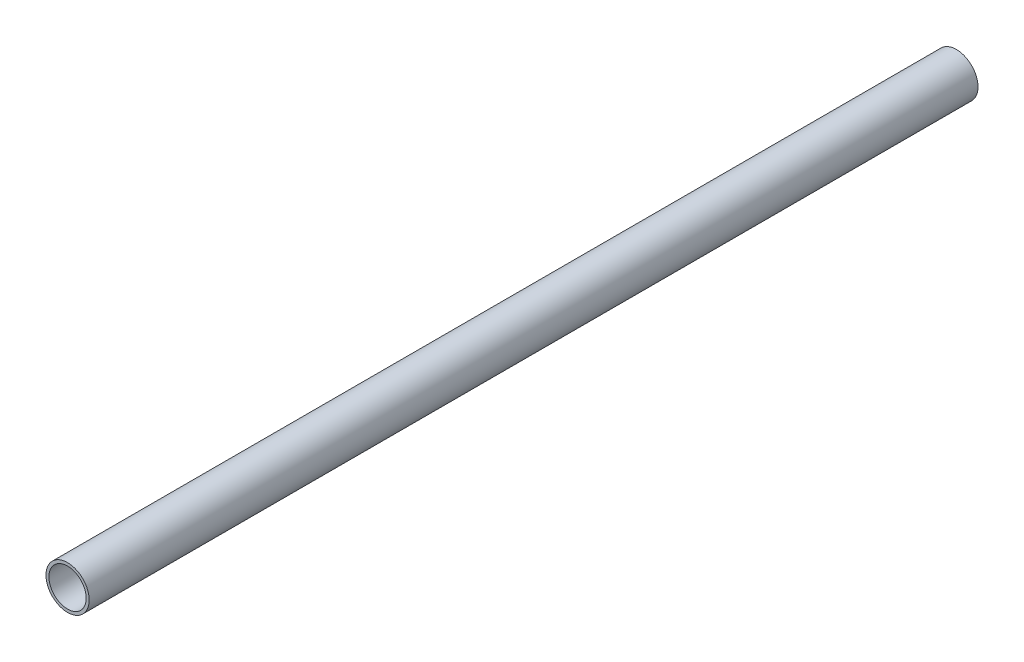
SolidWorks part; units mm, degrees
ref_plane "Front Plane" through (0, 0, 0) normal (0, 0, 1) x (1, 0, 0)
ref_plane "Top Plane" through (0, 0, 0) normal (0, 1, 0) x (1, 0, 0)
ref_plane "Right Plane" through (0, 0, 0) normal (1, 0, 0) x (0, 0, -1)
sketch "Sketch1" plane through (0, 0, 0) normal (0, 0, 1) x (1, 0, 0)
  circle A0 centre (0, 0) radius 22.225 construction
  circle A1 centre (0, 0) radius 19.177 construction
  point P3 (-22.225, 0)
  point P4 (22.225, 0)
  point P6 (-19.177, 0)
  point P7 (19.177, 0)
  dimension "OD" = 44.45
  dimension "Wall" = 3.048
  dimension "ID" = 38.354
sketch "Sketch2" plane through (0, 0, 0) normal (1, 0, 0) x (0, 0, -1)
  line L0 (457.2, 0) -> (-457.2, 0) construction
  line L2 (0, 22.225) -> (0, -22.225) construction
  line L3 (0, 22.225) -> (0, -22.225) construction
  line L4 (457.2, 22.225) -> (-457.2, 22.225) construction
  line L5 (457.2, -22.225) -> (-457.2, -22.225) construction
  line L6 (-457.2, -22.225) -> (-457.2, 22.225) construction
  line L7 (457.2, -22.225) -> (457.2, 22.225) construction
  line L8 (-412.75, -22.225) -> (-412.75, 22.225) construction
  line L9 (412.75, -22.225) -> (412.75, 22.225) construction
  point P3 (0, 0)
  point P9 (0, 22.225)
  point P11 (0, -22.225)
  point P13 (-457.2, 0)
  point P14 (457.2, 22.225)
  point P15 (-457.2, -22.225)
  point P16 (-457.2, 22.225)
  point P17 (-457.2, 0)
  point P18 (457.2, -22.225)
  point P19 (457.2, 0)
  point P22 (-412.75, 0)
  point P25 (412.75, 0)
  point P26 (-412.75, -22.225)
  point P27 (-412.75, 22.225)
  point P28 (412.75, 22.225)
  point P29 (412.75, -22.225)
  dimension "Length" = 914.4
  dimension "D1" = 44.45
sketch "Sketch3" plane through (0, 0, 0) normal (0, 0, 1) x (1, 0, 0)
  circle A0 centre (0, 0) radius 22.225 construction
  circle A1 centre (0, 0) radius 19.177 construction
  circle A2 centre (0, 0) radius 22.225
  circle A3 centre (0, 0) radius 19.177
extrude "Boss-Extrude1" add sketch "Sketch3" along normal mid plane 914.4
ref_plane "Plane1" through (22.225, 0, 0) normal (1, 0, 0) x (0, 0, -1)
sketch "Sketch4" plane through (22.225, 0, 0) normal (1, 0, 0) x (0, 0, -1)
  circle A0 centre (-438.7344, 0) radius 7.9382
equation "\"D1@Sketch2\"=\"OD@Sketch1\""
equation "\"D1@Boss-Extrude1\"=\"Length@Sketch2\""
